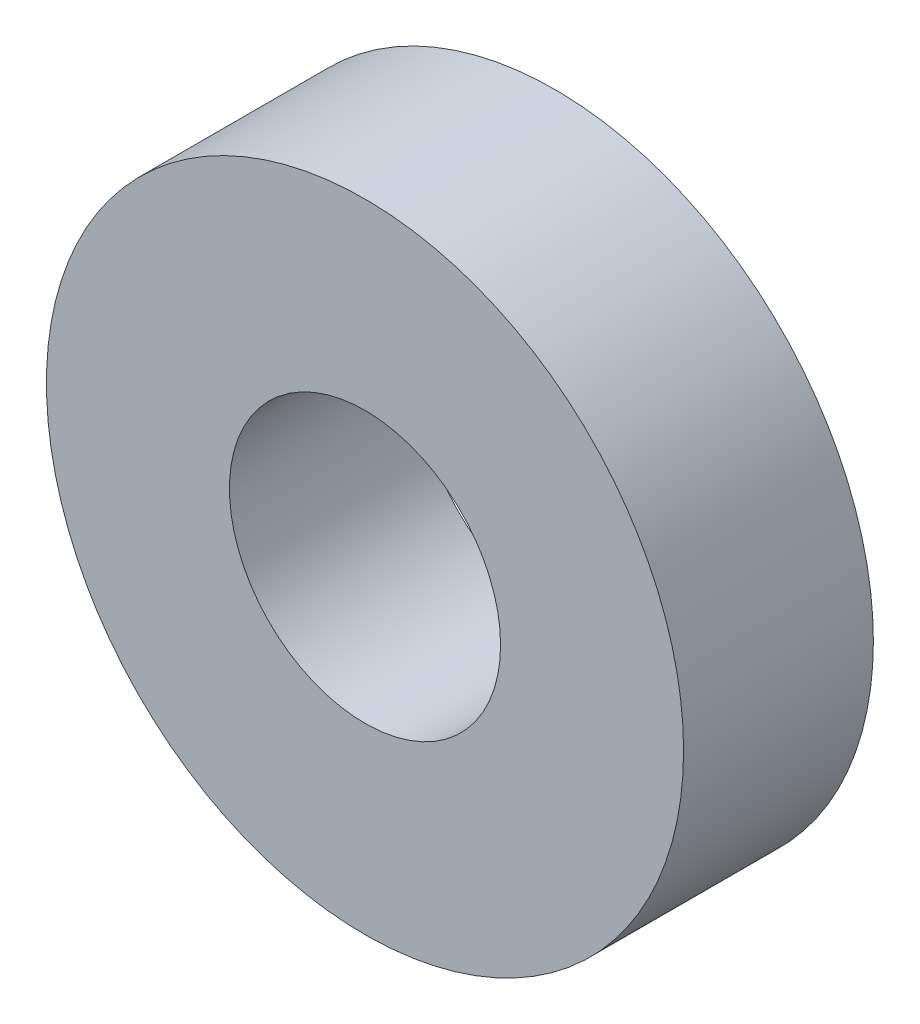
SolidWorks part; units mm, degrees
ref_plane "Спереди" through (0, 0, 0) normal (0, 0, 1) x (1, 0, 0)
ref_plane "Сверху" through (0, 0, 0) normal (0, 1, 0) x (1, 0, 0)
ref_plane "Справа" through (0, 0, 0) normal (1, 0, 0) x (0, 0, -1)
sketch "Эскиз1" plane through (0, 0, 0) normal (0, 0, 1) x (1, 0, 0)
  circle A0 centre (0, 0) radius 23.5
  circle A1 centre (0, 0) radius 10
extrude "Purchased_bearing_envelope" add sketch "Эскиз1" along normal blind 14 from offset 31
